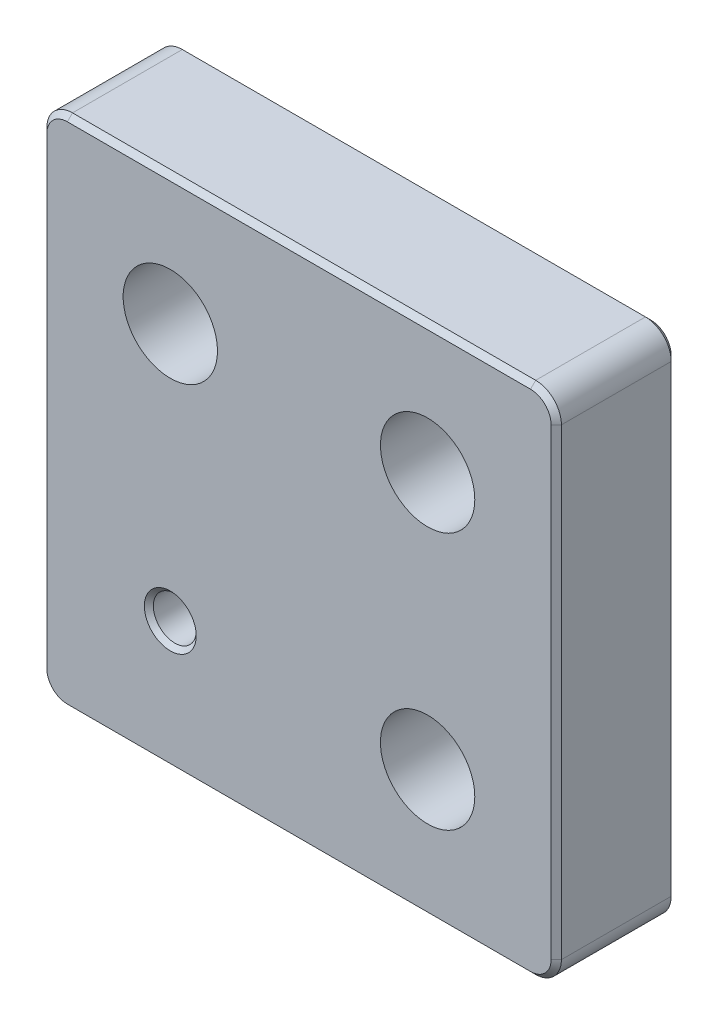
SolidWorks part; units mm, degrees
material "6061 Alloy"
ref_plane "Front Plane" through (0, 0, 0) normal (0, 0, 1) x (1, 0, 0)
ref_plane "Top Plane" through (0, 0, 0) normal (0, 1, 0) x (1, 0, 0)
ref_plane "Right Plane" through (0, 0, 0) normal (1, 0, 0) x (0, 0, -1)
sketch "Sketch1" plane through (0, 0, 0) normal (0, 0, 1) x (1, 0, 0)
  line L1 (30, -30) -> (-30, -30)
  line L2 (30, -30) -> (30, 30)
  line L3 (30, 30) -> (-30, 30)
  line L4 (-30, -30) -> (-30, 30)
  line L5 (30, -30) -> (-30, 30) construction
  line L6 (30, 30) -> (-30, -30) construction
  point P0 (0, 0)
  dimension "D1" = 60
  dimension "D2" = 60
extrude "Boss-Extrude1" add sketch "Sketch1" along normal blind 14
hole_wizard "CBORE for M6 Hex Socket Head Cap Screw1" positions "Sketch2" profile "Sketch4" counterbore size "M6" standard "DIN" end condition up to next
sketch "Sketch2" plane through (0, 0, 14) normal (0, 0, 1) x (1, 0, 0)
  line L0 (0, 0) -> (0, 30) construction
  line L1 (30, 30) -> (-30, 30) construction
  line L3 (0, 0) -> (30, 0) construction
  line L4 (30, -30) -> (30, 30) construction
  point P0 (-15, 15)
  point P2 (15, 15)
  point P4 (15, -15)
  dimension "D1" = 30
  dimension "D2" = 30
sketch "Sketch4" plane through (-15, 15, 14) normal (1, 0, 0) x (0, -1, 0)
  line L0 (0, 0) -> (0, 14)
  line L1 (0, 14) -> (3.25, 14)
  line L3 (3.25, 14) -> (3.25, 8)
  line L4 (3.25, 8) -> (5.5, 8)
  line L5 (5.5, 8) -> (5.5, 0)
  line L7 (5.5, 0) -> (0, 0)
  line L11 (0, -6.35) -> (0, 107.95) construction
  dimension "Thru Hole Dia." = 6.5
  dimension "Thru Hole Depth" = 14
  dimension "C'Bore Dia." = 11
  dimension "C'Bore Depth" = 8
hole_wizard "M6 Tapped Hole1" positions "Sketch5" profile "Sketch7" tap size "M6" standard "DIN" end condition up to next
sketch "Sketch5" plane through (0, 0, 14) normal (0, 0, 1) x (1, 0, 0)
  line L0 (-15, 15) -> (-15, -15) construction
  line L2 (-15, -15) -> (15, -15) construction
  point P0 (-15, -15)
sketch "Sketch7" plane through (-15, -15, 14) normal (1, 0, 0) x (0, -1, 0)
  line L0 (0, 0) -> (0, 14)
  line L1 (0, 14) -> (2.5, 14)
  line L2 (2.5, 14) -> (2.5, 0.525)
  line L3 (2.5, 0.525) -> (3.025, 0)
  line L5 (3.025, 0) -> (0, 0)
  line L6 (-2.5, 0.525) -> (-3.025, 0) construction
  line L11 (0, -6.35) -> (0, 107.95) construction
  dimension "Thru Tap Drill Dia." = 5
  dimension "Thru Tap Drill Depth" = 14
  dimension "Near C'Sink Dia." = 6.05
  dimension "Near C'Sink Angle" = 90
cosmetic thread "Hole Thread1"
fillet "Fillet1" radius 3 4 edges at (-30, 30, 7) (30, 30, 7) (30, -30, 7) (-30, -30, 7)
chamfer "Chamfer1" distance 0.6 angle 45 16 edges at (-29.1213, -29.1213, 0) (0, -30, 0) (29.1213, -29.1213, 0) (30, 0, 0) (29.1213, 29.1213, 0) (0, 30, 0) (-29.1213, 29.1213, 0) (-30, 0, 0) (29.1213, 29.1213, 14) (30, 0, 14) (29.1213, -29.1213, 14) (0, -30, 14) (-29.1213, -29.1213, 14) (-30, 0, 14) (-29.1213, 29.1213, 14) (0, 30, 14)
